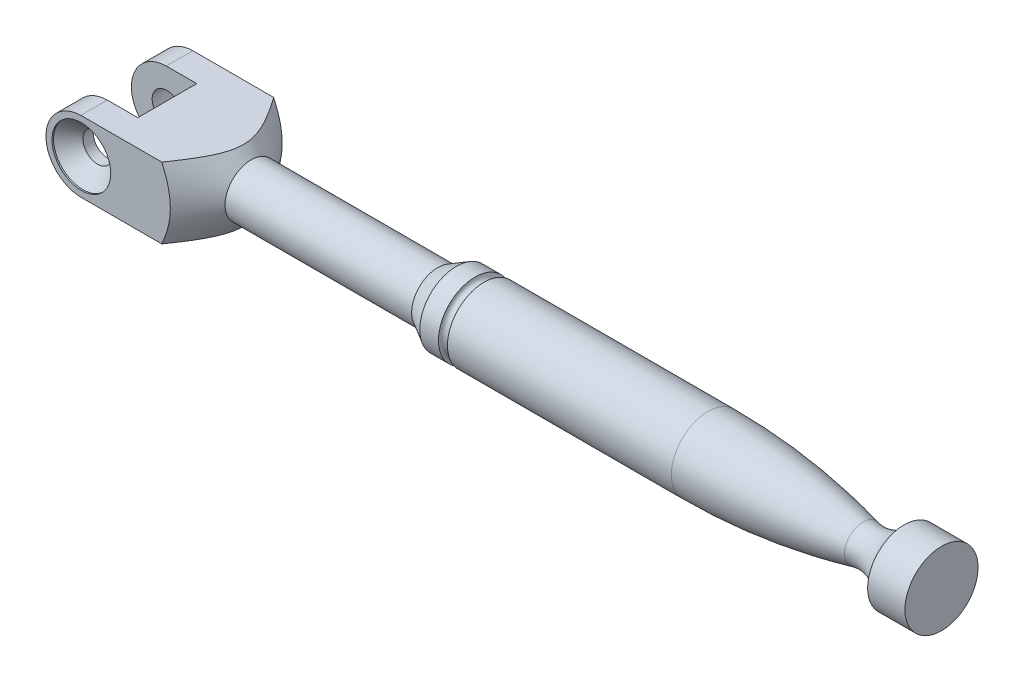
SolidWorks part; units mm, degrees
material "AISI Type A2 Tool Steel"
ref_plane "Front" through (0, 0, 0) normal (0, 0, 1) x (1, 0, 0)
ref_plane "Top" through (0, 0, 0) normal (0, 1, 0) x (1, 0, 0)
ref_plane "Right" through (0, 0, 0) normal (1, 0, 0) x (0, 0, -1)
sketch "Sketch1" plane through (0, 0, 0) normal (1, 0, 0) x (0, 0, -1)
  circle A0 centre (0, 0) radius 4.445
  dimension "D1" = 8.89
extrude "Boss-Extrude1" add sketch "Sketch1" along normal blind 41.275
sketch "Sketch3" plane through (0, 0, 0) normal (-1, 0, 0) x (0, 0, 1)
  line L1 (-9.525, -6.0325) -> (9.525, -6.0325)
  line L2 (-9.525, -6.0325) -> (-9.525, 6.0325)
  line L3 (-9.525, 6.0325) -> (9.525, 6.0325)
  line L4 (9.525, -6.0325) -> (9.525, 6.0325)
  line L5 (-9.525, -6.0325) -> (9.525, 6.0325) construction
  line L6 (-9.525, 6.0325) -> (9.525, -6.0325) construction
  point P0 (0, 0)
  dimension "D1" = 12.065
  dimension "D2" = 19.05
extrude "Boss-Extrude4" add sketch "Sketch3" along normal blind 19.05
sketch "Sketch4" plane through (-19.05, 0, 0) normal (-1, 0, 0) x (0, 0, 1)
  line L0 (9.525, 6.0325) -> (-9.525, 6.0325) construction
  line L1 (-5.0165, -6.0325) -> (5.0165, -6.0325)
  line L2 (-5.0165, -6.0325) -> (-5.0165, 6.0325)
  line L3 (-5.0165, 6.0325) -> (5.0165, 6.0325)
  line L4 (5.0165, -6.0325) -> (5.0165, 6.0325)
  line L5 (-5.0165, -6.0325) -> (5.0165, 6.0325) construction
  line L6 (-5.0165, 6.0325) -> (5.0165, -6.0325) construction
  point P0 (0, 0)
  dimension "D1" = 10.033
extrude "Cut-Extrude1" cut sketch "Sketch4" against normal blind 11.1252
sketch "Sketch5" plane through (0, 0, 9.525) normal (0, 0, 1) x (1, 0, 0)
  line L0 (-19.05, 0) -> (0, 0) construction
  line L1 (-19.05, -6.0325) -> (-19.05, 6.0325) construction
  line L2 (-19.05, 6.0325) -> (0, 6.0325) construction
  line L3 (-19.05, -6.0325) -> (0, -6.0325) construction
  line L4 (-13.1079, 6.0325) -> (-19.05, 6.0325)
  line L5 (-19.05, 6.0325) -> (-19.05, -6.0325)
  line L6 (-19.05, -6.0325) -> (-13.1079, -6.0325)
  arc A0 (-13.1079, 6.0325) -> (-13.1079, -6.0325) centre (-13.0168, 0) ccw
  point P12 (-19.05, 0)
  line M2 (0, 6.0325) -> (-19.05, 6.0325)
  line M3 (-19.05, 6.0325) -> (-19.05, -6.0325)
  line M4 (-19.05, -6.0325) -> (0, -6.0325)
  dimension "D1" = 6.0332
extrude "Cut-Extrude2" cut sketch "Sketch5" against normal through all contours A0 M2 M3 | A0 L5 M4
hole_wizard "CSK for M5 Flat Head Machine Screw1" positions "Sketch6" profile "Sketch7" countersink size "M5" standard "ANSI Metric"
sketch "Sketch6" plane through (0, 0, 9.525) normal (0, 0, 1) x (1, 0, 0)
  point P0 (-13.0168, 0)
sketch "Sketch7" plane through (-13.0168, 0, 9.525) normal (1, 0, 0) x (0, -1, 0)
  line L0 (0, 0) -> (0, 6.0097)
  line L1 (0, 6.0097) -> (2.5, 4.5075)
  line L2 (2.5, 4.5075) -> (2.5, 2.754)
  line L3 (2.5, 2.754) -> (5, 0.254)
  line L4 (5, 0.254) -> (5, 0)
  line L6 (5, 0) -> (0, 0)
  line L7 (-2.5, 2.754) -> (-5, 0.254) construction
  line L10 (0, 6.0097) -> (-2.5, 4.5075) construction
  line L11 (0, -6.35) -> (0, 107.95) construction
  dimension "Hole Dia." = 5
  dimension "Hole Depth" = 4.5075
  dimension "C'Sink Dia." = 10
  dimension "C'Sink Angle" = 90
  dimension "Drill Angle" = 118
  dimension "Head Clearance" = 0.254
hole_wizard "M5x0.8 Tapped Hole1" positions "Sketch15" profile "Sketch16" tap size "M5x0.8" standard "ANSI Metric"
sketch "Sketch15" plane through (0, 0, -5.0165) normal (0, 0, 1) x (1, 0, 0)
  point P0 (-13.0168, 0)
sketch "Sketch16" plane through (-13.0168, 0, -5.0165) normal (1, 0, 0) x (0, -1, 0)
  line L0 (0, 0) -> (0, 6.0097)
  line L1 (0, 6.0097) -> (2.5, 4.5075)
  line L2 (2.5, 4.5075) -> (2.5, 0)
  line L5 (2.5, 0) -> (0, 0)
  line L10 (0, 6.0097) -> (-2.5, 4.5075) construction
  line L11 (0, -6.35) -> (0, 107.95) construction
  dimension "Tap Drill Dia." = 5
  dimension "Tap Drill Depth" = 4.5075
  dimension "Drill Angle" = 118
cosmetic thread "Hole Thread1" parameters "D1"=4.5974, "D2"=5
sketch "Sketch9" plane through (0, 0, 0) normal (0, 1, 0) x (1, 0, 0)
  line L0 (0, -4.445) -> (6.35, -4.445)
  line L1 (0, -4.445) -> (41.275, -4.445) construction
  line L5 (0, 0) -> (32.8612, 0) construction
  line L6 (0, -4.445) -> (0, -12.065)
  line L7 (0, -12.065) -> (6.35, -4.445)
  dimension "D1" = 6.35
  dimension "D2" = 7.62
revolve "Revolve3" add sketch "Sketch9" angle 360 about L5
sketch "Sketch10" plane through (0, 0, 0) normal (-1, 0, 0) x (0, 0, 1)
  line L0 (-11.5259, 6.0325) -> (11.1284, 6.0325)
  line L1 (-11.5259, 6.0325) -> (-11.5259, 12.3825)
  line L2 (11.1284, 6.0325) -> (11.1284, 12.3825)
  line L3 (-11.5259, 12.3825) -> (11.1284, 12.3825)
  line L4 (-13.3523, 0) -> (14.4422, 0) construction
  line L5 (-11.5259, -6.0325) -> (11.1284, -6.0325)
  line L6 (11.1284, -6.0325) -> (11.1284, -12.3825)
  line L7 (-11.5259, -12.3825) -> (11.1284, -12.3825)
  line L8 (-11.5259, -6.0325) -> (-11.5259, -12.3825)
  dimension "D1" = 6.35
  dimension "D2" = 22.6543
extrude "Cut-Extrude3" cut sketch "Sketch10" against normal blind 7.62
sketch "Sketch11" plane through (0, 0, 0) normal (-1, 0, 0) x (0, 0, 1)
  line L0 (-9.525, 6.0325) -> (-9.525, -6.0325)
  line L1 (-9.525, 6.0325) -> (-12.8297, 6.0325)
  line L2 (-9.525, -6.0325) -> (-12.8297, -6.0325)
  line L3 (-12.8297, 6.0325) -> (-12.8297, -6.0325)
  line L4 (0, 8.1499) -> (0, -8.7606) construction
  line L5 (9.525, -6.0325) -> (12.8297, -6.0325)
  line L6 (9.525, 6.0325) -> (9.525, -6.0325)
  line L7 (12.8297, 6.0325) -> (12.8297, -6.0325)
  line L8 (9.525, 6.0325) -> (12.8297, 6.0325)
extrude "Cut-Extrude4" cut sketch "Sketch11" against normal blind 7.62
sketch "Sketch13" plane through (0, 0, 0) normal (0, 0, 1) x (1, 0, 0)
  line L0 (41.275, 0) -> (41.275, 6.223)
  line L1 (41.275, -4.445) -> (41.275, 4.445) construction
  line L2 (41.275, 0) -> (123.825, 0)
  line L3 (123.825, 0) -> (123.825, 6.223)
  line L4 (41.275, 6.223) -> (44.45, 6.223)
  line L5 (45.974, 6.223) -> (84.074, 6.223)
  line L6 (123.825, 6.223) -> (117.475, 6.223)
  arc A0 (44.45, 6.223) -> (45.974, 6.223) centre (45.212, 6.223) ccw
  arc A1 (84.074, 6.223) -> (110.4619, 3.1353) centre (84.074, -108.077) cw
  arc A2 (110.4619, 3.1353) -> (117.475, 6.223) centre (111.9279, 9.3137) ccw
  dimension "D4" = 0.762
  dimension "D7" = 114.3
  dimension "D8" = 6.35
  dimension "D1" = 6.223
  dimension "D2" = 82.55
  dimension "D3" = 3.175
  dimension "D5" = 38.1
  dimension "D6" = 6.35
revolve "Revolve4" add sketch "Sketch13" angle 360 about L2
sketch "Sketch14" plane through (0, 0, 0) normal (0, 0, 1) x (1, 0, 0)
  line L0 (41.275, 4.445) -> (38.1, 4.445)
  line L1 (41.275, 4.445) -> (6.35, 4.445) construction
  line L2 (38.1, 4.445) -> (41.275, 6.223)
  line L3 (41.275, 6.223) -> (41.275, 4.445)
  line L4 (0, 0) -> (54.1159, 0) construction
  dimension "D1" = 3.175
revolve "Revolve5" add sketch "Sketch14" angle 360 about L4
